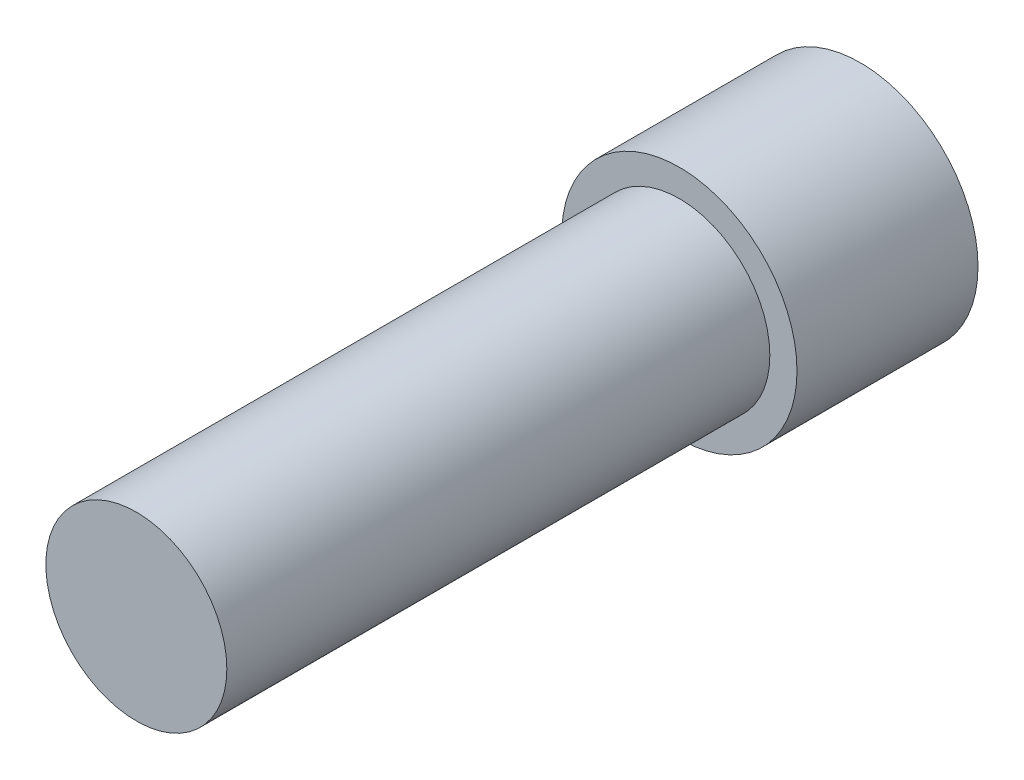
SolidWorks part; units mm, degrees
ref_plane "Front Plane" through (0, 0, 0) normal (0, 0, 1) x (1, 0, 0)
ref_plane "Top Plane" through (0, 0, 0) normal (0, 1, 0) x (1, 0, 0)
ref_plane "Right Plane" through (0, 0, 0) normal (1, 0, 0) x (0, 0, -1)
sketch "Sketch1" plane through (0, 0, 0) normal (0, 0, 1) x (1, 0, 0)
  circle A0 centre (0, 0) radius 6.5
  dimension "D1" = 13
extrude "Boss-Extrude1" add sketch "Sketch1" along normal blind 10
sketch "Sketch2" plane through (0, 0, 10) normal (0, 0, 1) x (1, 0, 0)
  circle A0 centre (0, 0) radius 5
  dimension "D1" = 10
extrude "Boss-Extrude2" add sketch "Sketch2" along normal blind 30
sketch "Sketch3" plane through (0, 0, 0) normal (0, 0, -1) x (-1, 0, 0)
  line L1 (4.5, 2.5981) -> (0, 5.1962)
  line L2 (0, 5.1962) -> (-4.5, 2.5981)
  line L3 (-4.5, 2.5981) -> (-4.5, -2.5981)
  line L4 (-4.5, -2.5981) -> (0, -5.1962)
  line L5 (0, -5.1962) -> (4.5, -2.5981)
  line L6 (4.5, -2.5981) -> (4.5, 2.5981)
  circle A0 centre (0, 0) radius 4.5 construction
  dimension "D1" = 9
extrude "Cut-Extrude1" cut sketch "Sketch3" against normal blind 5
